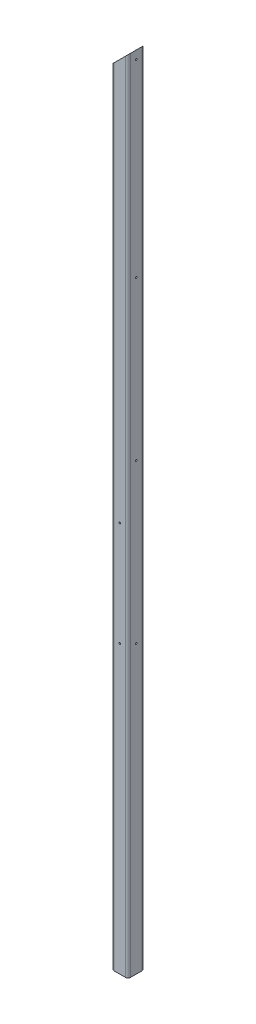
SolidWorks part; units mm, degrees
ref_plane "Front Plane" through (0, 0, 0) normal (0, 0, 1) x (1, 0, 0)
ref_plane "Top Plane" through (0, 0, 0) normal (0, 1, 0) x (1, 0, 0)
ref_plane "Right Plane" through (0, 0, 0) normal (1, 0, 0) x (0, 0, -1)
sketch "Sketch1" plane through (0, 0, 0) normal (0, 0, 1) x (1, 0, 0)
  line L0 (0, 0) -> (0, 1920)
  dimension "D1" = 1920
other "Tube (square) 40 X 40 X 3.2(1)"
ref_plane "Plane1" through (0, 0, 0) normal (0, 1, 0) x (-1, 0, 0)
sketch "Sketch15" plane through (0, 0, 0) normal (0, 1, 0) x (-1, 0, 0)
  line L0 (-13.6, -16.8) -> (13.6, -16.8)
  line L1 (-16.8, -13.6) -> (-16.8, 13.6)
  line L2 (13.6, 16.8) -> (-13.6, 16.8)
  line L3 (16.8, 13.6) -> (16.8, -13.6)
  line L4 (-13.6, -20) -> (13.6, -20)
  line L5 (-20, -13.6) -> (-20, 13.6)
  line L6 (13.6, 20) -> (-13.6, 20)
  line L7 (20, 13.6) -> (20, -13.6)
  line L8 (-20, 0) -> (-16.8, 0) construction
  line L9 (-16.8, 0) -> (16.8, 0) construction
  line L10 (16.8, 0) -> (20, 0) construction
  line L12 (0, 20) -> (0, 16.8) construction
  line L13 (0, 16.8) -> (0, -16.8) construction
  line L14 (0, -16.8) -> (0, -20) construction
  arc A0 (20, 13.6) -> (13.6, 20) centre (13.6, 13.6) ccw
  arc A1 (13.6, -20) -> (20, -13.6) centre (13.6, -13.6) ccw
  arc A2 (-20, -13.6) -> (-13.6, -20) centre (-13.6, -13.6) ccw
  arc A3 (-13.6, 20) -> (-20, 13.6) centre (-13.6, 13.6) ccw
  arc A4 (-13.6, 16.8) -> (-16.8, 13.6) centre (-13.6, 13.6) ccw
  arc A5 (16.8, 13.6) -> (13.6, 16.8) centre (13.6, 13.6) ccw
  arc A6 (13.6, -16.8) -> (16.8, -13.6) centre (13.6, -13.6) ccw
  arc A7 (-16.8, -13.6) -> (-13.6, -16.8) centre (-13.6, -13.6) ccw
  point P2 (-20, 20)
  point P33 (-20, -20)
  point P34 (20, -20)
  point P36 (20, 20)
  point P37 (0, 0)
  dimension "D1" = 6.4
  dimension "Thickness" = 3.2
  dimension "V_leg" = 40
  dimension "H_leg" = 40
ref_plane "Plane2" through (0, 0, -20) normal (0, 0, -1) x (-1, 0, 0)
sketch "Sketch13" plane through (0, 0, -20) normal (0, 0, -1) x (-1, 0, 0)
  line L2 (20, 1920) -> (20, 0) construction
  line L3 (20, 1920) -> (20, 1880)
  line L4 (-13.6, 1920) -> (13.6, 1920) construction
  line L5 (-20, 1920) -> (20, 1920)
  line L9 (20, 1880) -> (-20, 1920)
  line L10 (20, 1920) -> (20, 1880)
  dimension "D1" = 40
extrude "Cut-Extrude1" cut sketch "Sketch13" against normal through all contours L9 L3 L5
ref_plane "Plane3" through (20, 0, 0) normal (1, 0, 0) x (0, 0, -1)
sketch "Sketch16" plane through (20, 0, 0) normal (1, 0, 0) x (0, 0, -1)
  line L0 (-13.6, 1920) -> (13.6, 1920) construction
  line L1 (-13.6, 1920) -> (13.6, 1920) construction
  line L2 (-13.6, 1900) -> (13.6, 1900) construction
  line L3 (-13.6, 1447) -> (13.6, 1447) construction
  line L4 (-13.6, 1067) -> (13.6, 1067) construction
  line L5 (-13.6, 687) -> (13.6, 687) construction
  circle A0 centre (0, 1900) radius 2
  circle A1 centre (0, 1447) radius 2
  circle A2 centre (0, 1067) radius 2
  circle A3 centre (0, 687) radius 2
  dimension "D4" = 4
  dimension "D5" = 1233
  dimension "D1" = 20
  dimension "D2" = 453
  dimension "D3" = 833
extrude "Cut-Extrude2" cut sketch "Sketch16" against normal blind 3
ref_plane "Plane4" through (0, 0, 20) normal (0, 0, 1) x (1, 0, 0)
sketch "Sketch17" plane through (0, 0, 20) normal (0, 0, 1) x (1, 0, 0)
  line L0 (-13.6, 687) -> (13.6, 687) construction
  line L1 (-13.6, 0) -> (13.6, 0) construction
  line L2 (-13.6, 0) -> (13.6, 0) construction
  circle A0 centre (0, 687) radius 2
  circle A1 centre (0, 937) radius 2
  dimension "D2" = 4
  dimension "D4" = 250
  dimension "D1" = 687
  dimension "D3" = 2
extrude "Cut-Extrude3" cut sketch "Sketch17" against normal blind 3
